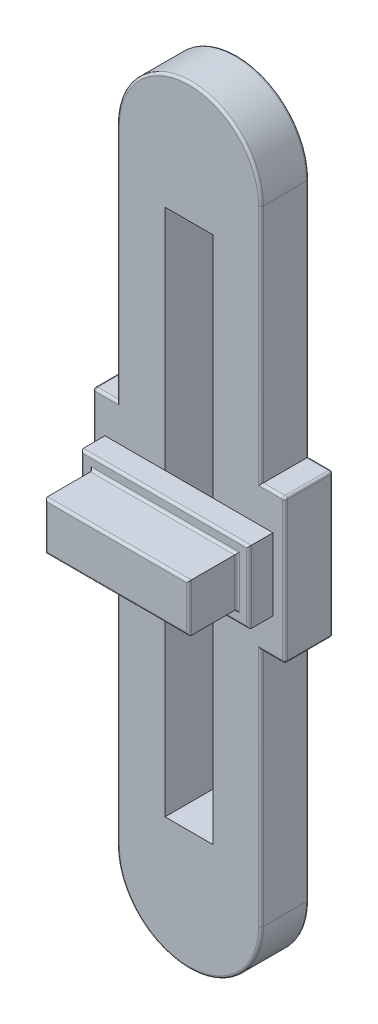
SolidWorks part; units mm, degrees
ref_plane "Front Plane" through (0, 0, 0) normal (0, 0, 1) x (1, 0, 0)
ref_plane "Top Plane" through (0, 0, 0) normal (0, 1, 0) x (1, 0, 0)
ref_plane "Right Plane" through (0, 0, 0) normal (1, 0, 0) x (0, 0, -1)
sketch "Sketch2" plane through (0, 0, 0) normal (0, 0, 1) x (1, 0, 0)
  line L0 (0, 0) -> (0, -260) construction
  line L1 (30, 0) -> (30, -100)
  line L2 (-30, 0) -> (-30, -100)
  line L3 (-30, -130) -> (30, -130) construction
  line L4 (-10, -20) -> (10, -20)
  line L5 (-10, -20) -> (-10, -240)
  line L6 (-10, -240) -> (10, -240)
  line L7 (10, -20) -> (10, -240)
  line L8 (-10, -20) -> (10, -240) construction
  line L9 (-10, -240) -> (10, -20) construction
  line L10 (-30, -160) -> (-30, -260)
  line L11 (-30, -100) -> (-40, -100)
  line L13 (-30, -160) -> (-40, -160)
  line L14 (-40, -100) -> (-40, -160)
  line L15 (30, -100) -> (40, -100)
  line L17 (30, -160) -> (40, -160)
  line L18 (40, -100) -> (40, -160)
  line L19 (30, -160) -> (30, -260)
  line L20 (40, -130) -> (46.8887, -130) construction
  arc A0 (30, 0) -> (-30, 0) centre (0, 0) ccw
  arc A1 (-30, -260) -> (30, -260) centre (0, -260) ccw
  point P3 (0, -130)
  point P8 (0, -130)
  point P23 (0, 0)
  point P24 (0, 0)
  dimension "D2" = 30
  dimension "D1" = 260
  dimension "D3" = 20
  dimension "D4" = 220
  dimension "D5" = 10
  dimension "D6" = 60
  dimension "D7" = 20
extrude "Boss-Extrude1" add sketch "Sketch2" along normal blind 20
sketch "Sketch3" plane through (0, 0, 20) normal (0, 0, 1) x (1, 0, 0)
  line L0 (-40, -130) -> (40, -130) construction
  line L1 (-40, -100) -> (-40, -160) construction
  line L2 (40, -160) -> (40, -100) construction
  line L4 (-30, -120) -> (30, -120)
  line L5 (-30, -120) -> (-30, -140)
  line L6 (-30, -140) -> (30, -140)
  line L7 (30, -120) -> (30, -140)
  line L8 (-30, -120) -> (30, -140) construction
  line L9 (-30, -140) -> (30, -120) construction
  point P6 (0, -130)
  dimension "D1" = 60
  dimension "D2" = 20
extrude "Boss-Extrude2" add sketch "Sketch3" along normal blind 30
sketch "Sketch4" plane through (0, 0, 20) normal (0, 0, 1) x (1, 0, 0)
  line L0 (35, -115) -> (-35, -115)
  line L1 (-35, -115) -> (-35, -145)
  line L2 (-35, -145) -> (35, -145)
  line L3 (35, -145) -> (35, -115)
  line L4 (30, -140) -> (30, -120)
  line L5 (30, -120) -> (-30, -120)
  line L6 (-30, -120) -> (-30, -140)
  line L7 (-30, -140) -> (30, -140)
  line L8 (30, -140) -> (30, -120)
  line L9 (30, -120) -> (-30, -120)
  line L10 (-30, -120) -> (-30, -140)
  line L11 (-30, -140) -> (30, -140)
  dimension "D1" = 0
  dimension "D2" = 5
extrude "Boss-Extrude3" add sketch "Sketch4" along normal blind 10
fillet "Fillet1" radius 1 12 edges at (0, -120, 30) (-30, -130, 30) (0, -140, 30) (30, -130, 30) (0, -145, 30) (-35, -130, 30) (0, -115, 30) (35, -130, 30) (0, -140, 50) (-30, -130, 50) (0, -120, 50) (30, -130, 50)
fillet "Fillet2" radius 1 16 edges at (-30, -210, 0) (0, -290, 0) (30, -50, 0) (-30, -50, 0) (30, -210, 20) (0, -290, 20) (30, -50, 20) (0, 30, 20) (-40, -130, 0) (30, -210, 0) (40, -130, 0) (0, 30, 0) (40, -130, 20) (-30, -210, 20) (-40, -130, 20) (-30, -50, 20)
fillet "Fillet3" radius 1 20 edges at (-34, -160, 0) (-39.7071, -160, 0.2929) (-40, -160, 10) (-39.7071, -160, 19.7071) (34, -160, 0) (39.7071, -160, 0.2929) (40, -160, 10) (39.7071, -160, 19.7071) (34, -100, 0) (39.7071, -100, 0.2929) (40, -100, 10) (39.7071, -100, 19.7071) (-34, -100, 0) (-39.7071, -100, 0.2929) (-40, -100, 10) (-39.7071, -100, 19.7071) (-34, -160, 20) (34, -160, 20) (34, -100, 20) (-34, -100, 20)
